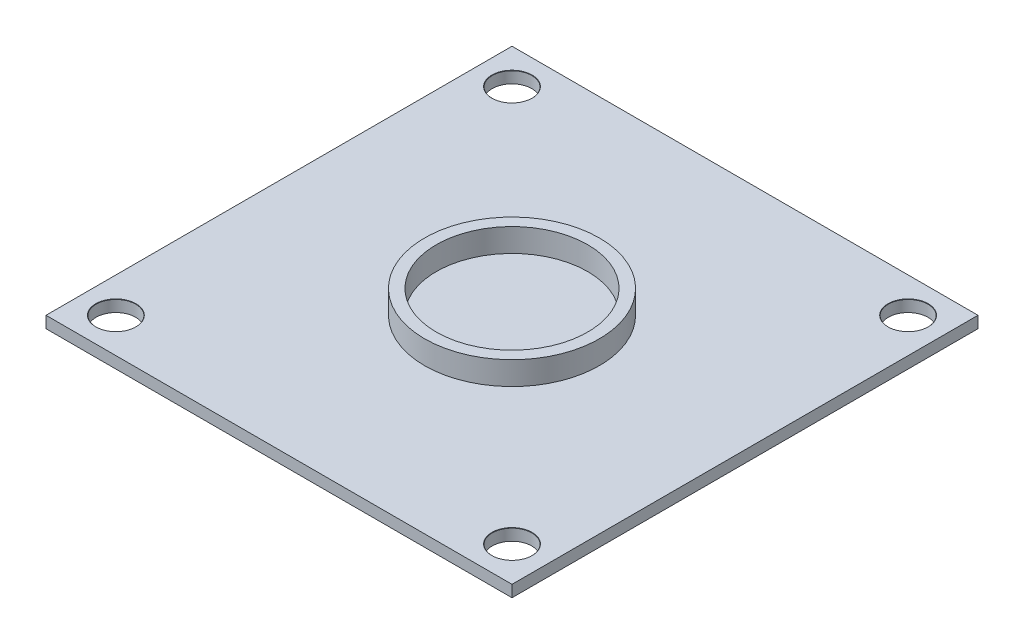
SolidWorks part; units mm, degrees
ref_plane "Front Plane" through (0, 0, 0) normal (0, 0, 1) x (1, 0, 0)
ref_plane "Top Plane" through (0, 0, 0) normal (0, 1, 0) x (1, 0, 0)
ref_plane "Right Plane" through (0, 0, 0) normal (1, 0, 0) x (0, 0, -1)
sketch "Sketch1" plane through (0, 0, 0) normal (0, 1, 0) x (1, 0, 0)
  line L1 (0, 0) -> (40, 0)
  line L2 (0, 0) -> (0, 40)
  line L3 (0, 40) -> (40, 40)
  line L4 (40, 0) -> (40, 40)
  dimension "D1" = 40
extrude "Boss-Extrude1" add sketch "Sketch1" along normal blind 1
sketch "Sketch2" plane through (0, 1, 0) normal (0, 1, 0) x (1, 0, 0)
  line L0 (40, 40) -> (0, 40) construction
  line L1 (0, 40) -> (0, 0) construction
  circle A0 centre (20, 20) radius 7.5
  circle A1 centre (20, 20) radius 6.5
  point P7 (20, 40)
  point P10 (0, 20)
  dimension "D1" = 1
  dimension "D2" = 15
extrude "Boss-Extrude2" add sketch "Sketch2" along normal blind 2
hole_wizard "M3 Clearance Hole1" positions "Sketch3" profile "Sketch4" hole size "M3" standard "ANSI Metric" end condition through all
sketch "Sketch3" plane through (0, 1, 0) normal (0, 1, 0) x (1, 0, 0)
  line L0 (0, 0) -> (40, 0) construction
  line L1 (0, 40) -> (0, 0) construction
  line L2 (20, 0) -> (20, 40) construction
  line L3 (40, 40) -> (0, 40) construction
  line L5 (40, 20) -> (0, 20) construction
  line L6 (40, 0) -> (40, 40) construction
  line L8 (3, 3) -> (37, 3) construction
  line L9 (3, 37) -> (3, 3) construction
  point P0 (3, 3)
  point P2 (3, 37)
  point P4 (37, 37)
  point P6 (37, 3)
  point P31 (20, 3)
  point P39 (3, 20)
  point P40 (4, 2.7456)
  point P41 (0, 0)
  dimension "D1" = 34
  dimension "D2" = 34
sketch "Sketch4" plane through (3, 1, -3) normal (1, 0, 0) x (0, 0, 1)
  line L0 (0, 0) -> (0, 1)
  line L1 (0, 1) -> (1.7, 1)
  line L2 (1.7, 1) -> (1.7, 0.025)
  line L3 (1.7, 0.025) -> (1.725, 0)
  line L5 (1.725, 0) -> (0, 0)
  line L6 (-1.7, 0.025) -> (-1.725, 0) construction
  line L11 (0, -6.35) -> (0, 107.95) construction
  dimension "Thru Hole Dia." = 3.4
  dimension "Thru Hole Depth" = 1
  dimension "Near C'Sink Dia." = 3.45
  dimension "Near C'Sink Angle" = 90
